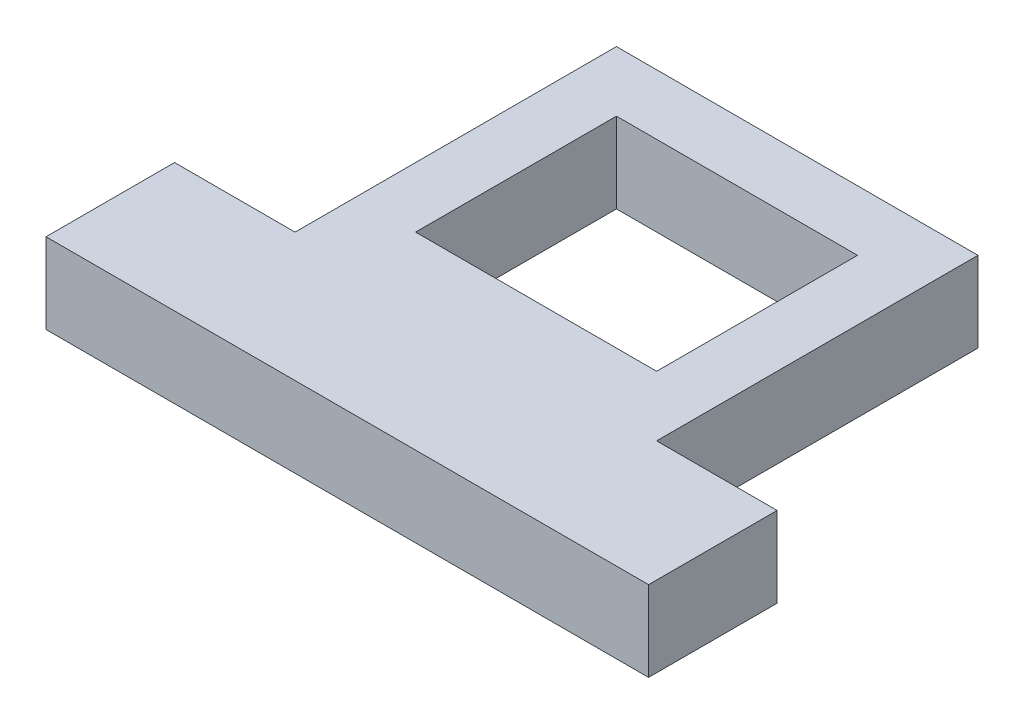
SolidWorks part; units mm, degrees
ref_plane "Front Plane" through (0, 0, 0) normal (0, 0, 1) x (1, 0, 0)
ref_plane "Top Plane" through (0, 0, 0) normal (0, 1, 0) x (1, 0, 0)
ref_plane "Right Plane" through (0, 0, 0) normal (1, 0, 0) x (0, 0, -1)
sketch "Sketch1" plane through (0, 0, 0) normal (0, 1, 0) x (1, 0, 0)
  line L0 (-4.5, -4) -> (4.5, -4)
  line L1 (-3, 2.5) -> (3, 2.5)
  line L2 (-3, 2.5) -> (-3, -2.5)
  line L3 (-3, -2.5) -> (3, -2.5)
  line L4 (3, 2.5) -> (3, -2.5)
  line L5 (-3, 2.5) -> (3, -2.5) construction
  line L6 (-3, -2.5) -> (3, 2.5) construction
  line L7 (4.5, 4) -> (4.5, -4)
  line L8 (-4.5, 4) -> (4.5, 4)
  line L9 (-4.5, 4) -> (-4.5, -4)
  point P0 (0, 0)
  dimension "D1" = 5
  dimension "D2" = 6
  dimension "D3" = 1.5
extrude "Boss-Extrude1" add sketch "Sketch1" along normal blind 2
sketch "Sketch2" plane through (0, 0, 0) normal (0, 1, 0) x (1, 0, 0)
  line L1 (7.5, -4) -> (-7.5, -4)
  line L2 (7.5, -4) -> (7.5, -7.2)
  line L3 (7.5, -7.2) -> (-7.5, -7.2)
  line L4 (-7.5, -4) -> (-7.5, -7.2)
  point P4 (0, -4)
  dimension "D1" = 3.2
  dimension "D2" = 15
  dimension "D3" = 4
extrude "Boss-Extrude3" add sketch "Sketch2" along normal blind 2
